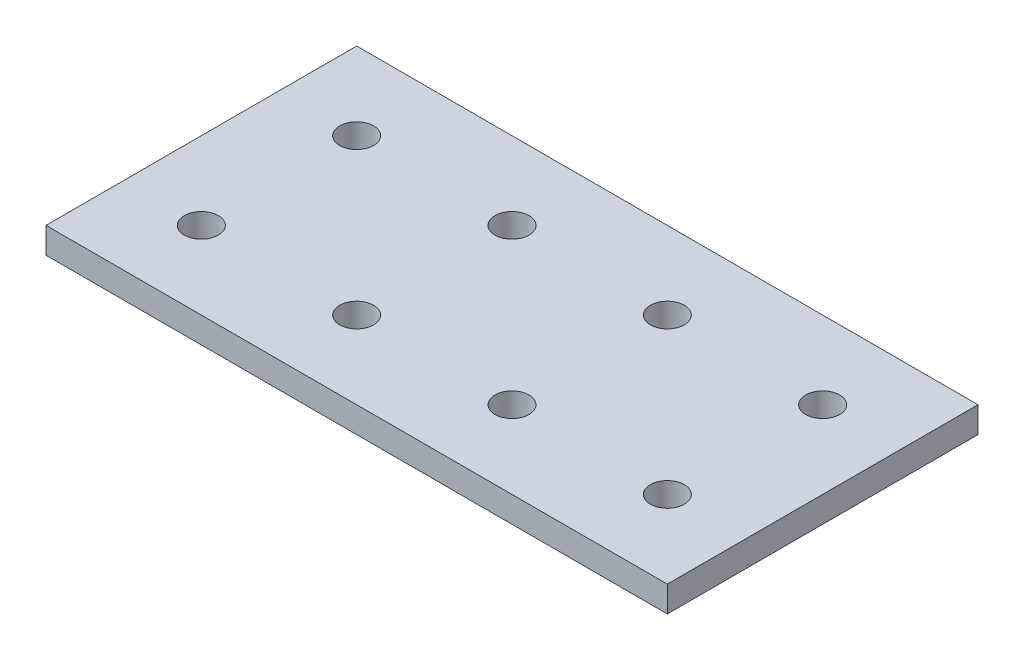
SolidWorks part; units mm, degrees
material "6061-T6 (SS)"
ref_plane "Front" through (0, 0, 0) normal (0, 0, 1) x (1, 0, 0)
ref_plane "Top" through (0, 0, 0) normal (0, 1, 0) x (1, 0, 0)
ref_plane "Right" through (0, 0, 0) normal (1, 0, 0) x (0, 0, -1)
sketch "Sketch1" plane through (0, 0, 0) normal (0, 1, 0) x (1, 0, 0)
  line L1 (0, 0) -> (152.4, 0)
  line L2 (0, 0) -> (0, 76.2)
  line L3 (0, 76.2) -> (152.4, 76.2)
  line L4 (152.4, 0) -> (152.4, 76.2)
  dimension "D1" = 152.4
  dimension "D2" = 76.2
extrude "Boss-Extrude1" add sketch "Sketch1" along normal blind 6.35
hole_wizard "21/64 (0.32813) Diameter Hole1" positions "Sketch2" profile "Sketch3" hole size "21/64" standard "ANSI Inch" end condition up to next
sketch "Sketch2" plane through (0, 6.35, 0) normal (0, 1, 0) x (1, 0, 0)
  line L0 (152.4, 76.2) -> (0, 76.2) construction
  line L1 (0, 76.2) -> (0, 0) construction
  point P0 (19.05, 57.15)
  dimension "D1" = 19.05
  dimension "D2" = 19.05
sketch "Sketch3" plane through (19.05, 6.35, -57.15) normal (1, 0, 0) x (0, 0, 1)
  line L0 (0, 0) -> (0, 6.35)
  line L1 (0, 6.35) -> (4.1673, 6.35)
  line L2 (4.1673, 6.35) -> (4.1673, 0)
  line L5 (4.1673, 0) -> (0, 0)
  line L11 (0, -6.35) -> (0, 107.95) construction
  dimension "Thru Hole Dia." = 8.3345
  dimension "Thru Hole Depth" = 6.35
pattern_linear "LPattern1" count 2 spacing 38.1 along (0, 0, 1) count 4 spacing 38.1 along (1, 0, 0) of "21/64 (0.32813) Diameter Hole1"
